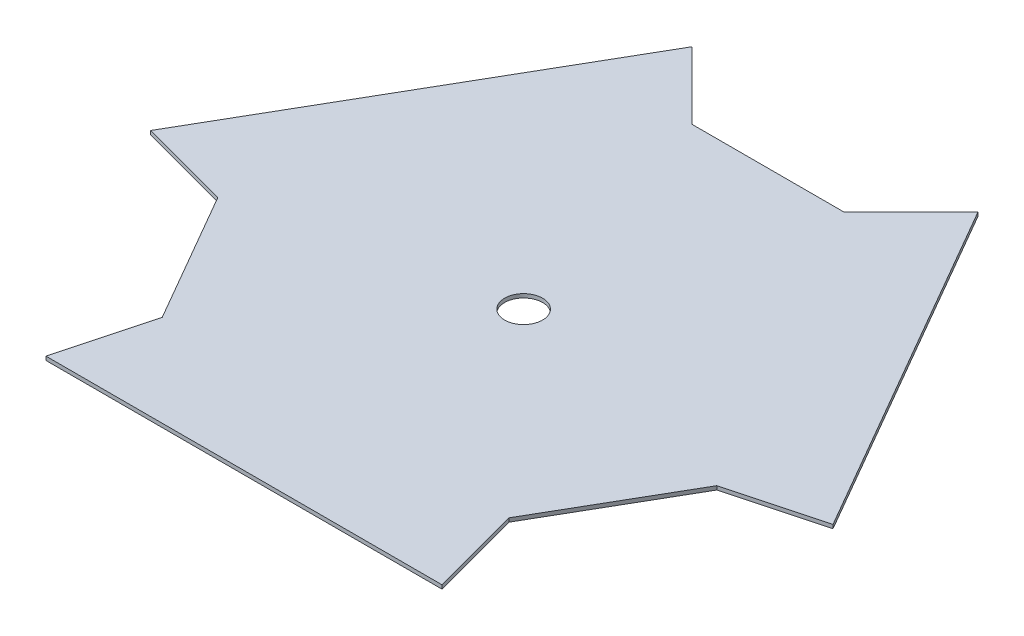
SolidWorks part; units mm, degrees
ref_plane "Front Plane" through (0, 0, 0) normal (0, 0, 1) x (1, 0, 0)
ref_plane "Top Plane" through (0, 0, 0) normal (0, 1, 0) x (1, 0, 0)
ref_plane "Right Plane" through (0, 0, 0) normal (1, 0, 0) x (0, 0, -1)
sketch "Sketch1" plane through (0, 0, 0) normal (0, 1, 0) x (1, 0, 0)
  line L0 (-30, -18) -> (30, -18) construction
  line L1 (-30, 10) -> (-22.5, 10) construction
  line L2 (-46.46, 5.4904) -> (-53.96, -7.5) construction
  line L3 (-30, -10) -> (-22.5, -10) construction
  line L4 (30, 10) -> (30, 2.5) construction
  line L5 (0, 0) -> (0, -75.5561) construction
  line L6 (38.6603, -23) -> (51.362, -45) construction
  line L7 (55.7735, -52.641) -> (58.3716, -51.141) construction
  line L8 (59.1036, -48.409) -> (41.8357, -18.5) construction
  line L9 (43.1036, -13.7679) -> (55.6921, -6.5) construction
  line L10 (56.4241, -3.7679) -> (51.362, 5) construction
  line L11 (25.3812, 20) -> (-25.3812, 20) construction
  line L12 (43.5677, -13.5) -> (36.0677, -0.5096) construction
  line L13 (36.0677, -0.5096) -> (46.46, 5.4904) construction
  line L14 (46.46, 5.4904) -> (53.96, -7.5) construction
  line L15 (-36.0677, -0.5096) -> (-46.46, 5.4904) construction
  line L16 (-43.5677, -13.5) -> (-36.0677, -0.5096) construction
  line L17 (-56.4241, -3.7679) -> (-51.362, 5) construction
  line L18 (-43.1036, -13.7679) -> (-55.6921, -6.5) construction
  line L19 (-59.1036, -48.409) -> (-41.8357, -18.5) construction
  line L20 (-55.7735, -52.641) -> (-58.3716, -51.141) construction
  line L21 (-38.6603, -23) -> (-51.362, -45) construction
  line L22 (-30, 10) -> (-30, 2.5) construction
  line L23 (30, 2.5) -> (25, 2.5) construction
  line L24 (25, 2.5) -> (25, -2.5) construction
  line L25 (25, -2.5) -> (30, -2.5) construction
  line L26 (30, -2.5) -> (30, -10) construction
  line L27 (22.5, -10) -> (22.5, -5) construction
  line L28 (22.5, -5) -> (17.5, -5) construction
  line L29 (17.5, -5) -> (17.5, -10) construction
  line L30 (22.5, -10) -> (30, -10) construction
  line L31 (17.5, 10) -> (17.5, 9) construction
  line L32 (17.5, 9) -> (22.5, 9) construction
  line L33 (22.5, 9) -> (22.5, 10) construction
  line L34 (22.5, 10) -> (30, 10) construction
  line L35 (2.5, -10) -> (2.5, -5) construction
  line L36 (2.5, -5) -> (-2.5, -5) construction
  line L37 (-2.5, -5) -> (-2.5, -10) construction
  line L38 (-2.5, 10) -> (-2.5, 9) construction
  line L39 (-2.5, 9) -> (2.5, 9) construction
  line L40 (2.5, 9) -> (2.5, 10) construction
  line L41 (-17.5, -10) -> (-17.5, -5) construction
  line L42 (-17.5, -5) -> (-22.5, -5) construction
  line L43 (-22.5, -5) -> (-22.5, -10) construction
  line L44 (-22.5, 10) -> (-22.5, 9) construction
  line L45 (-22.5, 9) -> (-17.5, 9) construction
  line L46 (-17.5, 9) -> (-17.5, 10) construction
  line L47 (-17.5, 10) -> (-2.5, 10) construction
  line L48 (-17.5, -10) -> (-2.5, -10) construction
  line L49 (2.5, -10) -> (17.5, -10) construction
  line L50 (2.5, 10) -> (17.5, 10) construction
  line L51 (-25, -2.5) -> (-30, -2.5) construction
  line L52 (-25, 2.5) -> (-25, -2.5) construction
  line L53 (-30, 2.5) -> (-25, 2.5) construction
  line L54 (-30, -2.5) -> (-30, -10) construction
  line L55 (-54.8261, -52) -> (54.8261, -52) construction
  line L56 (-49.6299, -48) -> (49.6299, -48) construction
  line L57 (-55.6921, -52.5) -> (-55.7735, -52.641) construction
  line L58 (55.6921, -52.5) -> (55.7735, -52.641) construction
  line L59 (207.8868, -326.1089) -> (177.8868, -378.0704) construction
  line L60 (232.1355, -340.1089) -> (228.3855, -346.6041) construction
  line L61 (214.815, -330.1089) -> (211.065, -336.6041) construction
  line L62 (202.1355, -392.0704) -> (195.6403, -388.3204) construction
  line L63 (169.2265, -383.0704) -> (143.8231, -383.0704) construction
  line L64 (135, -383.0704) -> (135, -386.0704) construction
  line L65 (137, -388.0704) -> (171.5359, -388.0704) construction
  line L66 (175, -391.5345) -> (175, -406.0704) construction
  line L67 (177, -408.0704) -> (187.1244, -408.0704) construction
  line L68 (213.1051, -393.0704) -> (238.4863, -349.1089) construction
  line L69 (233.4241, -310.3409) -> (238.4863, -319.1089) construction
  line L70 (218.1036, -316.8768) -> (230.6921, -309.6089) construction
  line L71 (196.1036, -285.6999) -> (213.3716, -315.6089) construction
  line L72 (190.7735, -286.4679) -> (193.3716, -284.9679) construction
  line L73 (207.8868, -316.1089) -> (195.185, -294.1089) construction
  line L74 (232.1355, -340.1089) -> (225.6403, -336.3589) construction
  line L75 (195.6403, -388.3204) -> (198.1403, -383.9903) construction
  line L76 (198.1403, -383.9903) -> (193.8101, -381.4903) construction
  line L77 (193.8101, -381.4903) -> (191.3101, -385.8204) construction
  line L78 (191.3101, -385.8204) -> (184.815, -382.0704) construction
  line L79 (188.565, -375.5752) -> (192.8951, -378.0752) construction
  line L80 (192.8951, -378.0752) -> (195.3951, -373.7451) construction
  line L81 (195.3951, -373.7451) -> (191.065, -371.2451) construction
  line L82 (188.565, -375.5752) -> (184.815, -382.0704) construction
  line L83 (208.3855, -381.2451) -> (207.5194, -380.7451) construction
  line L84 (207.5194, -380.7451) -> (205.0194, -385.0752) construction
  line L85 (205.0194, -385.0752) -> (205.8855, -385.5752) construction
  line L86 (205.8855, -385.5752) -> (202.1355, -392.0704) construction
  line L87 (198.565, -358.2547) -> (202.8951, -360.7547) construction
  line L88 (202.8951, -360.7547) -> (205.3951, -356.4246) construction
  line L89 (205.3951, -356.4246) -> (201.065, -353.9246) construction
  line L90 (218.3855, -363.9246) -> (217.5194, -363.4246) construction
  line L91 (217.5194, -363.4246) -> (215.0194, -367.7547) construction
  line L92 (215.0194, -367.7547) -> (215.8855, -368.2547) construction
  line L93 (208.565, -340.9342) -> (212.8951, -343.4342) construction
  line L94 (212.8951, -343.4342) -> (215.3951, -339.1041) construction
  line L95 (215.3951, -339.1041) -> (211.065, -336.6041) construction
  line L96 (228.3855, -346.6041) -> (227.5194, -346.1041) construction
  line L97 (227.5194, -346.1041) -> (225.0194, -350.4342) construction
  line L98 (225.0194, -350.4342) -> (225.8855, -350.9342) construction
  line L99 (225.8855, -350.9342) -> (218.3855, -363.9246) construction
  line L100 (208.565, -340.9342) -> (201.065, -353.9246) construction
  line L101 (198.565, -358.2547) -> (191.065, -371.2451) construction
  line L102 (215.8855, -368.2547) -> (208.3855, -381.2451) construction
  line L103 (218.8101, -338.189) -> (221.3101, -333.8589) construction
  line L104 (223.1403, -340.689) -> (218.8101, -338.189) construction
  line L105 (225.6403, -336.3589) -> (223.1403, -340.689) construction
  line L106 (221.3101, -333.8589) -> (214.815, -330.1089) construction
  line L107 (190.8549, -287.6089) -> (136.0289, -382.5704) construction
  line L108 (191.7209, -294.1089) -> (142.091, -380.0704) construction
  line L109 (190.8549, -286.6089) -> (190.7735, -286.4679) construction
  line L110 (135.1628, -383.0704) -> (135, -383.0704) construction
  line L111 (236.46, -323.5993) -> (228.96, -310.6089) construction
  line L112 (175, -392.0704) -> (190, -392.0704) construction
  line L113 (190, -392.0704) -> (190, -404.0704) construction
  line L114 (190, -404.0704) -> (175, -404.0704) construction
  line L115 (226.0677, -329.5993) -> (236.46, -323.5993) construction
  line L116 (218.5677, -316.6089) -> (226.0677, -329.5993) construction
  line L117 (-177.8868, -378.0704) -> (-207.8868, -326.1089) construction
  line L118 (-202.1355, -392.0704) -> (-205.8855, -385.5752) construction
  line L119 (-184.815, -382.0704) -> (-188.565, -375.5752) construction
  line L120 (-232.1355, -340.1089) -> (-225.6403, -336.3589) construction
  line L121 (-207.8868, -316.1089) -> (-195.185, -294.1089) construction
  line L122 (-190.7735, -286.4679) -> (-193.3716, -284.9679) construction
  line L123 (-196.1036, -285.6999) -> (-213.3716, -315.6089) construction
  line L124 (-218.1036, -316.8768) -> (-230.6921, -309.6089) construction
  line L125 (-233.4241, -310.3409) -> (-238.4863, -319.1089) construction
  line L126 (-238.4863, -349.1089) -> (-213.1051, -393.0704) construction
  line L127 (-177, -408.0704) -> (-187.1244, -408.0704) construction
  line L128 (-175, -391.5345) -> (-175, -406.0704) construction
  line L129 (-137, -388.0704) -> (-171.5359, -388.0704) construction
  line L130 (-135, -383.0704) -> (-135, -386.0704) construction
  line L131 (-169.2265, -383.0704) -> (-143.8231, -383.0704) construction
  line L132 (-202.1355, -392.0704) -> (-195.6403, -388.3204) construction
  line L133 (-225.6403, -336.3589) -> (-223.1403, -340.689) construction
  line L134 (-223.1403, -340.689) -> (-218.8101, -338.189) construction
  line L135 (-218.8101, -338.189) -> (-221.3101, -333.8589) construction
  line L136 (-221.3101, -333.8589) -> (-214.815, -330.1089) construction
  line L137 (-211.065, -336.6041) -> (-215.3951, -339.1041) construction
  line L138 (-215.3951, -339.1041) -> (-212.8951, -343.4342) construction
  line L139 (-212.8951, -343.4342) -> (-208.565, -340.9342) construction
  line L140 (-211.065, -336.6041) -> (-214.815, -330.1089) construction
  line L141 (-225.8855, -350.9342) -> (-225.0194, -350.4342) construction
  line L142 (-225.0194, -350.4342) -> (-227.5194, -346.1041) construction
  line L143 (-227.5194, -346.1041) -> (-228.3855, -346.6041) construction
  line L144 (-228.3855, -346.6041) -> (-232.1355, -340.1089) construction
  line L145 (-201.065, -353.9246) -> (-205.3951, -356.4246) construction
  line L146 (-205.3951, -356.4246) -> (-202.8951, -360.7547) construction
  line L147 (-202.8951, -360.7547) -> (-198.565, -358.2547) construction
  line L148 (-215.8855, -368.2547) -> (-215.0194, -367.7547) construction
  line L149 (-215.0194, -367.7547) -> (-217.5194, -363.4246) construction
  line L150 (-217.5194, -363.4246) -> (-218.3855, -363.9246) construction
  line L151 (-191.065, -371.2451) -> (-195.3951, -373.7451) construction
  line L152 (-195.3951, -373.7451) -> (-192.8951, -378.0752) construction
  line L153 (-192.8951, -378.0752) -> (-188.565, -375.5752) construction
  line L154 (-205.8855, -385.5752) -> (-205.0194, -385.0752) construction
  line L155 (-205.0194, -385.0752) -> (-207.5194, -380.7451) construction
  line L156 (-207.5194, -380.7451) -> (-208.3855, -381.2451) construction
  line L157 (-208.3855, -381.2451) -> (-215.8855, -368.2547) construction
  line L158 (-191.065, -371.2451) -> (-198.565, -358.2547) construction
  line L159 (-201.065, -353.9246) -> (-208.565, -340.9342) construction
  line L160 (-218.3855, -363.9246) -> (-225.8855, -350.9342) construction
  line L161 (-193.8101, -381.4903) -> (-191.3101, -385.8204) construction
  line L162 (-198.1403, -383.9903) -> (-193.8101, -381.4903) construction
  line L163 (-195.6403, -388.3204) -> (-198.1403, -383.9903) construction
  line L164 (-191.3101, -385.8204) -> (-184.815, -382.0704) construction
  line L165 (-136.0289, -382.5704) -> (-190.8549, -287.6089) construction
  line L166 (-142.091, -380.0704) -> (-191.7209, -294.1089) construction
  line L167 (-135.1628, -383.0704) -> (-135, -383.0704) construction
  line L168 (-190.8549, -286.6089) -> (-190.7735, -286.4679) construction
  line L169 (-190, -404.0704) -> (-175, -404.0704) construction
  line L170 (-218.5677, -316.6089) -> (-226.0677, -329.5993) construction
  line L171 (-226.0677, -329.5993) -> (-236.46, -323.5993) construction
  line L172 (-236.46, -323.5993) -> (-228.96, -310.6089) construction
  line L173 (-190, -392.0704) -> (-190, -404.0704) construction
  line L174 (-175, -392.0704) -> (-190, -392.0704) construction
  line L175 (-132.8534, -388.0704) -> (132.8534, -388.0704)
  line L176 (-132.8534, -388.0704) -> (-194.0303, -282.1089)
  line L177 (-194.0303, -282.1089) -> (-61.1769, -52)
  line L178 (-61.1769, -52) -> (61.1769, -52)
  line L179 (61.1769, -52) -> (194.0303, -282.1089)
  line L181 (132.8534, -388.0704) -> (194.0303, -282.1089)
  circle A0 centre (0, 0) radius 31.6228 construction
  arc A1 (30, -18) -> (38.6603, -23) centre (30, -28) cw construction
  arc A2 (51.362, 5) -> (25.3812, 20) centre (25.3812, -10) ccw construction
  arc A3 (41.1036, -13.7679) -> (40.1036, -17.5) centre (40.1036, -15.5) ccw construction
  arc A4 (58.3716, -51.141) -> (59.1036, -48.409) centre (57.3716, -49.409) ccw construction
  arc A5 (55.6921, -6.5) -> (56.4241, -3.7679) centre (54.6921, -4.7679) ccw construction
  arc A6 (40.1036, -17.5) -> (41.8357, -18.5) centre (40.1036, -19.5) cw construction
  arc A7 (41.1036, -13.7679) -> (43.1036, -13.7679) centre (42.1036, -12.0359) ccw construction
  arc A8 (-41.1036, -13.7679) -> (-43.1036, -13.7679) centre (-42.1036, -12.0359) cw construction
  arc A9 (-40.1036, -17.5) -> (-41.8357, -18.5) centre (-40.1036, -19.5) ccw construction
  arc A10 (-55.6921, -6.5) -> (-56.4241, -3.7679) centre (-54.6921, -4.7679) cw construction
  arc A11 (-58.3716, -51.141) -> (-59.1036, -48.409) centre (-57.3716, -49.409) cw construction
  arc A12 (-41.1036, -13.7679) -> (-40.1036, -17.5) centre (-40.1036, -15.5) cw construction
  arc A13 (-51.362, 5) -> (-25.3812, 20) centre (-25.3812, -10) cw construction
  arc A14 (-30, -18) -> (-38.6603, -23) centre (-30, -28) ccw construction
  arc A15 (55.6921, -52.5) -> (54.8261, -52) centre (54.8261, -53) ccw construction
  arc A16 (-54.8261, -52) -> (-55.6921, -52.5) centre (-54.8261, -53) ccw construction
  arc A17 (49.6299, -48) -> (51.362, -45) centre (49.6299, -46) ccw construction
  arc A18 (-49.6299, -48) -> (-51.362, -45) centre (-49.6299, -46) cw construction
  circle A19 centre (0, -240.7264) radius 147.344 construction
  arc A20 (177.8868, -378.0704) -> (169.2265, -383.0704) centre (169.2265, -373.0704) cw construction
  arc A21 (187.1244, -408.0704) -> (213.1051, -393.0704) centre (187.1244, -378.0704) ccw construction
  arc A22 (176, -389.8025) -> (173.2679, -387.0704) centre (175, -388.0704) ccw construction
  arc A23 (135, -386.0704) -> (137, -388.0704) centre (137, -386.0704) ccw construction
  arc A24 (175, -406.0704) -> (177, -408.0704) centre (177, -406.0704) ccw construction
  arc A25 (173.2679, -387.0704) -> (171.5359, -388.0704) centre (171.5359, -386.0704) cw construction
  arc A26 (176, -389.8025) -> (175, -391.5345) centre (177, -391.5345) ccw construction
  arc A27 (217.1036, -318.6089) -> (218.1036, -316.8768) centre (219.1036, -318.6089) cw construction
  arc A28 (213.3716, -317.6089) -> (213.3716, -315.6089) centre (211.6395, -316.6089) ccw construction
  arc A29 (230.6921, -309.6089) -> (233.4241, -310.3409) centre (231.6921, -311.3409) cw construction
  arc A30 (193.3716, -284.9679) -> (196.1036, -285.6999) centre (194.3716, -286.6999) cw construction
  arc A31 (217.1036, -318.6089) -> (213.3716, -317.6089) centre (215.1036, -318.6089) cw construction
  arc A32 (238.4863, -319.1089) -> (238.4863, -349.1089) centre (212.5056, -334.1089) cw construction
  arc A33 (207.8868, -326.1089) -> (207.8868, -316.1089) centre (199.2265, -321.1089) ccw construction
  arc A34 (135.1628, -383.0704) -> (136.0289, -382.5704) centre (135.1628, -382.0704) ccw construction
  arc A35 (190.8549, -287.6089) -> (190.8549, -286.6089) centre (189.9889, -287.1089) ccw construction
  arc A36 (142.091, -380.0704) -> (143.8231, -383.0704) centre (143.8231, -381.0704) ccw construction
  arc A37 (191.7209, -294.1089) -> (195.185, -294.1089) centre (193.453, -295.1089) cw construction
  arc A38 (-207.8868, -326.1089) -> (-207.8868, -316.1089) centre (-199.2265, -321.1089) cw construction
  arc A39 (-238.4863, -319.1089) -> (-238.4863, -349.1089) centre (-212.5056, -334.1089) ccw construction
  arc A40 (-217.1036, -318.6089) -> (-213.3716, -317.6089) centre (-215.1036, -318.6089) ccw construction
  arc A41 (-193.3716, -284.9679) -> (-196.1036, -285.6999) centre (-194.3716, -286.6999) ccw construction
  arc A42 (-230.6921, -309.6089) -> (-233.4241, -310.3409) centre (-231.6921, -311.3409) ccw construction
  arc A43 (-213.3716, -317.6089) -> (-213.3716, -315.6089) centre (-211.6395, -316.6089) cw construction
  arc A44 (-217.1036, -318.6089) -> (-218.1036, -316.8768) centre (-219.1036, -318.6089) ccw construction
  arc A45 (-176, -389.8025) -> (-175, -391.5345) centre (-177, -391.5345) cw construction
  arc A46 (-173.2679, -387.0704) -> (-171.5359, -388.0704) centre (-171.5359, -386.0704) ccw construction
  arc A47 (-175, -406.0704) -> (-177, -408.0704) centre (-177, -406.0704) cw construction
  arc A48 (-135, -386.0704) -> (-137, -388.0704) centre (-137, -386.0704) cw construction
  arc A49 (-176, -389.8025) -> (-173.2679, -387.0704) centre (-175, -388.0704) cw construction
  arc A50 (-187.1244, -408.0704) -> (-213.1051, -393.0704) centre (-187.1244, -378.0704) cw construction
  arc A51 (-177.8868, -378.0704) -> (-169.2265, -383.0704) centre (-169.2265, -373.0704) ccw construction
  arc A52 (-190.8549, -286.6089) -> (-190.8549, -287.6089) centre (-189.9889, -287.1089) ccw construction
  arc A53 (-136.0289, -382.5704) -> (-135.1628, -383.0704) centre (-135.1628, -382.0704) ccw construction
  arc A54 (-191.7209, -294.1089) -> (-195.185, -294.1089) centre (-193.453, -295.1089) ccw construction
  arc A55 (-142.091, -380.0704) -> (-143.8231, -383.0704) centre (-143.8231, -381.0704) cw construction
  point P7 (-57.4241, -5.5)
  point P9 (0, -18)
  point P22 (35.7735, -18)
  point P27 (0, 10)
  point P30 (60.1036, -50.141)
  point P33 (57.4241, -5.5)
  point P61 (0, 20)
  point P65 (-60.1036, -50.141)
  point P66 (-35.7735, -18)
  point P104 (55.4034, -52)
  point P107 (-55.4034, -52)
  point P120 (232.4241, -308.6089)
  point P122 (192.8868, -352.0897)
  point P137 (217.1355, -366.0897)
  point P169 (225.7957, -371.0897)
  point P173 (195.1036, -283.9679)
  point P174 (210.7735, -321.1089)
  point P222 (-175, -408.0704)
  point P224 (-192.8868, -352.0897)
  point P239 (-217.1355, -366.0897)
  point P271 (-225.7957, -371.0897)
  point P275 (-135, -388.0704)
  point P276 (-175, -383.0704)
  point P320 (0, -240.7264)
  dimension "D12" = 10
  dimension "D14" = 30
  dimension "D16" = 2
  dimension "D17" = 2
  dimension "D28" = 1
  dimension "D29" = 2
  dimension "D2" = 30
  dimension "D3" = 5
  dimension "D4" = 8
  dimension "D5" = 40
  dimension "D6" = 20
  dimension "D7" = 350
  dimension "D8" = 10
  dimension "D9" = 4
  dimension "D10" = 12
  dimension "D11" = 15
  dimension "D13" = 20
  dimension "D15" = 34
  dimension "D18" = 5
  dimension "D19" = 2.5
  dimension "D20" = 5
  dimension "D21" = 5
  dimension "D22" = 5
  dimension "D23" = 7.5
  dimension "D24" = 1
  dimension "D26" = 20
  dimension "D27" = 4
  dimension "D25" = 3
  dimension "D30" = 3
extrude "Boss-Extrude1" add sketch "Sketch1" along normal blind 2
sketch "Sketch2" plane through (0, 2, 0) normal (0, 1, 0) x (1, 0, 0)
  line L0 (194.0303, -282.1089) -> (61.1769, -52) construction
  line L1 (-61.1769, -52) -> (-194.0303, -282.1089) construction
  line L2 (-132.8534, -388.0704) -> (132.8534, -388.0704) construction
  circle A0 centre (0, -240.7264) radius 147.344 construction
  circle A1 centre (0, -240.7264) radius 10
  dimension "D1" = 20
extrude "Cut-Extrude1" cut sketch "Sketch2" against normal through all
sketch "Sketch4" plane through (0, 2, 0) normal (0, 1, 0) x (1, 0, 0)
  line L0 (-75.4055, -76.6447) -> (-40.0502, -112)
  line L1 (-61.1769, -52) -> (-194.0303, -282.1089) construction
  line L2 (-40.0502, -112) -> (40.0502, -112)
  line L3 (40.0502, -112) -> (75.4055, -76.6447)
  line L4 (194.0303, -282.1089) -> (61.1769, -52) construction
  line L5 (61.1769, -52) -> (-61.1769, -52) construction
  line L6 (179.8017, -257.4642) -> (131.5055, -270.4052)
  line L7 (131.5055, -270.4052) -> (91.4553, -339.7741)
  line L8 (91.4553, -339.7741) -> (104.3962, -388.0704)
  line L9 (-104.3962, -388.0704) -> (-91.4553, -339.7741)
  line L10 (-91.4553, -339.7741) -> (-131.5055, -270.4052)
  line L11 (-131.5055, -270.4052) -> (-179.8017, -257.4642)
  line L12 (75.4055, -76.6447) -> (179.8017, -257.4642)
  line L13 (-104.3962, -388.0704) -> (104.3962, -388.0704)
  line L14 (-179.8017, -257.4642) -> (-75.4055, -76.6447)
  circle A1 centre (0, -240.7264) radius 10 construction
  point P21 (0, -240.7264)
  dimension "D1" = 45
  dimension "D2" = 60
  dimension "D3" = 50
  dimension "D4" = 50
  dimension "D6" = 45
  dimension "D5" = 3
extrude "Cut-Extrude2" cut sketch "Sketch4" against normal blind 3 flip side to cut
